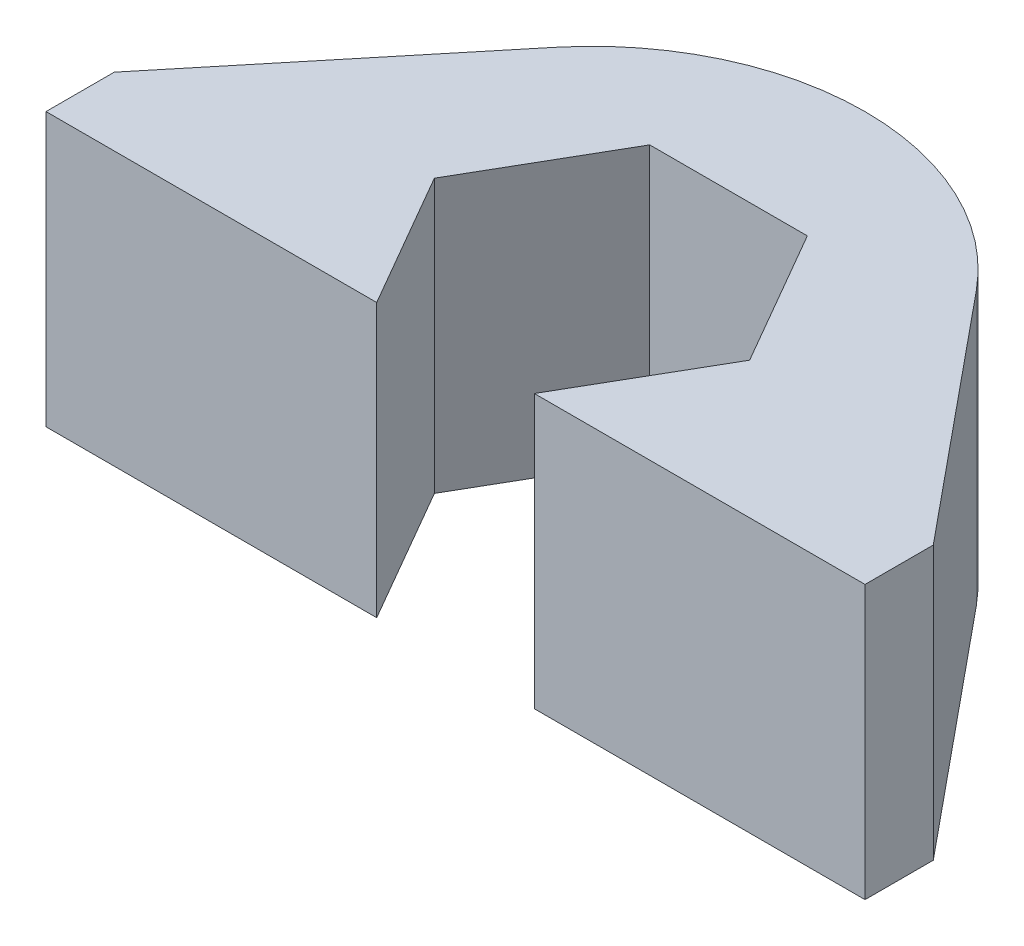
SolidWorks part; units mm, degrees
ref_plane "Front Plane" through (0, 0, 0) normal (0, 0, 1) x (1, 0, 0)
ref_plane "Top Plane" through (0, 0, 0) normal (0, 1, 0) x (1, 0, 0)
ref_plane "Right Plane" through (0, 0, 0) normal (1, 0, 0) x (0, 0, -1)
sketch "Sketch1" plane through (0, 0, 0) normal (0, 1, 0) x (1, 0, 0)
  line L0 (19.05, -6.35) -> (-19.05, -6.35)
  line L1 (7.3323, 0) -> (3.6662, 6.35)
  line L2 (3.6662, 6.35) -> (-3.6662, 6.35)
  line L3 (-3.6662, 6.35) -> (-7.3323, 0)
  line L4 (-7.3323, 0) -> (-3.6662, -6.35)
  line L5 (-3.6662, -6.35) -> (3.6662, -6.35)
  line L6 (3.6662, -6.35) -> (7.3323, 0)
  line L7 (-19.05, -6.35) -> (-19.05, -3.175)
  line L8 (19.05, -6.35) -> (19.05, -3.175)
  line L9 (-19.05, -3.175) -> (-9.8108, 8.0647)
  line L10 (19.05, -3.175) -> (9.8108, 8.0647)
  circle A0 centre (0, 0) radius 6.35 construction
  arc A2 (9.8108, 8.0647) -> (-9.8108, 8.0647) centre (0, 0) ccw
  point P12 (0, -6.35)
  dimension "D1" = 12.7
  dimension "D2" = 3.175
  dimension "D3" = 3.175
extrude "Boss-Extrude1" add sketch "Sketch1" along normal blind 12.7 contours L10 A2 L9 L7 L0 L4 L3 L2 L1 L6 L8
